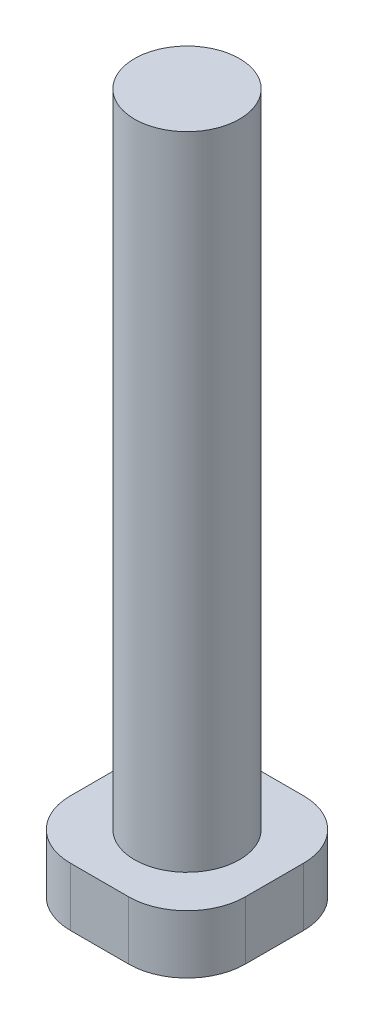
SolidWorks part; units mm, degrees
ref_plane "Front Plane" through (0, 0, 0) normal (0, 0, 1) x (1, 0, 0)
ref_plane "Top Plane" through (0, 0, 0) normal (0, 1, 0) x (1, 0, 0)
ref_plane "Right Plane" through (0, 0, 0) normal (1, 0, 0) x (0, 0, -1)
sketch "Sketch1" plane through (0, 0, 0) normal (0, 1, 0) x (1, 0, 0)
  line L1 (0, 0) -> (7.62, 0)
  line L2 (0, 0) -> (0, 7.62)
  line L3 (0, 7.62) -> (7.62, 7.62)
  line L4 (7.62, 0) -> (7.62, 7.62)
  dimension "D1" = 7.62
  dimension "D2" = 7.62
extrude "Boss-Extrude1" add sketch "Sketch1" along normal blind 30.48
sketch "Sketch2" plane through (0, 30.48, 0) normal (0, 1, 0) x (1, 0, 0)
  line L1 (0, 7.62) -> (7.62, 7.62)
  line L2 (0, 7.62) -> (0, 0)
  line L3 (0, 0) -> (7.62, 0)
  line L4 (7.62, 7.62) -> (7.62, 0)
  circle A0 centre (3.81, 3.81) radius 2.286
  dimension "D1" = 4.572
extrude "Cut-Extrude1" cut sketch "Sketch2" against normal blind 27.94
fillet "Fillet1" radius 2.54 1 edges at (7.62, 1.27, 0)
fillet "Fillet2" radius 2.54 1 edges at (7.62, 1.27, -7.62)
fillet "Fillet3" radius 2.54 1 edges at (0, 1.27, 0)
fillet "Fillet4" radius 2.54 1 edges at (0, 1.27, -7.62)
